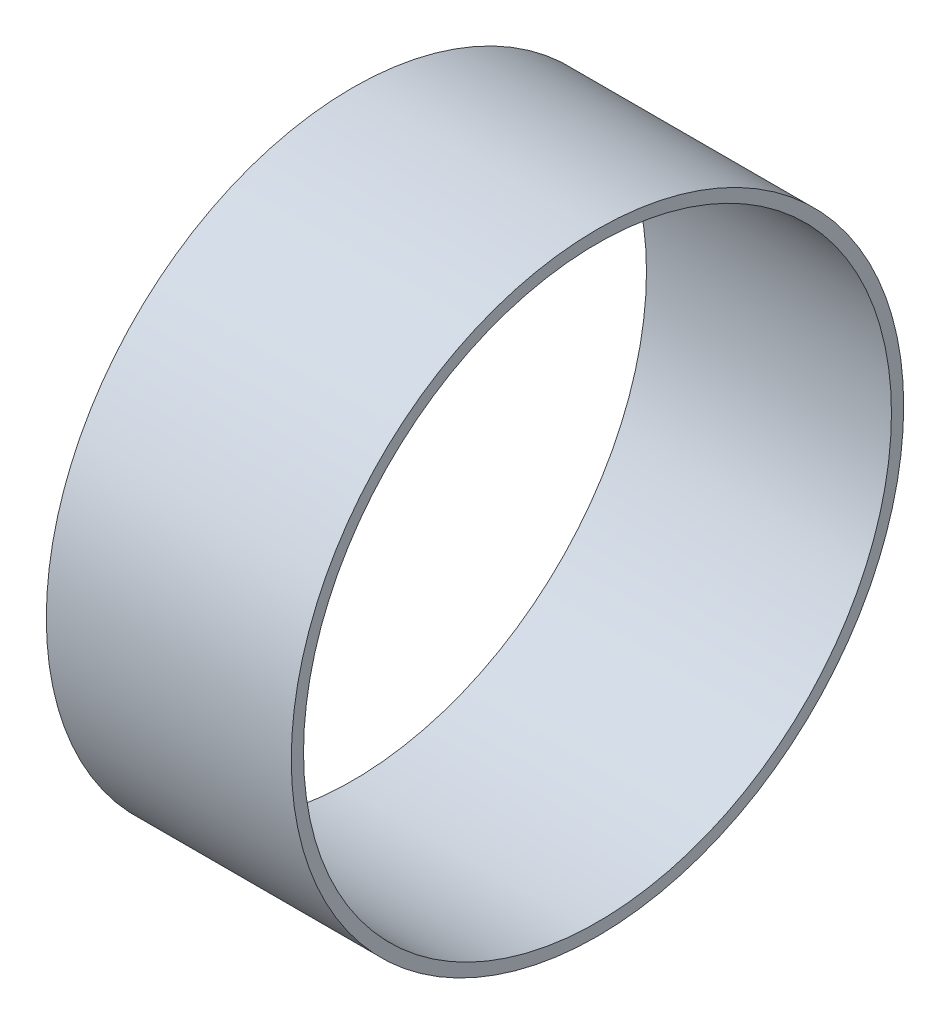
SolidWorks part; units mm, degrees
ref_plane "Plano frontal" through (0, 0, 0) normal (0, 0, 1) x (1, 0, 0)
ref_plane "Plano superior" through (0, 0, 0) normal (0, 1, 0) x (1, 0, 0)
ref_plane "Plano direito" through (0, 0, 0) normal (1, 0, 0) x (0, 0, -1)
sketch "Esboço1" plane through (0, 0, 0) normal (1, 0, 0) x (0, 0, -1)
  circle A0 centre (0, 0) radius 12
  circle A1 centre (0, 0) radius 12.5
  dimension "D1" = 24
  dimension "D2" = 25
extrude "Ressalto-extrusão1" add sketch "Esboço1" along normal blind 10
